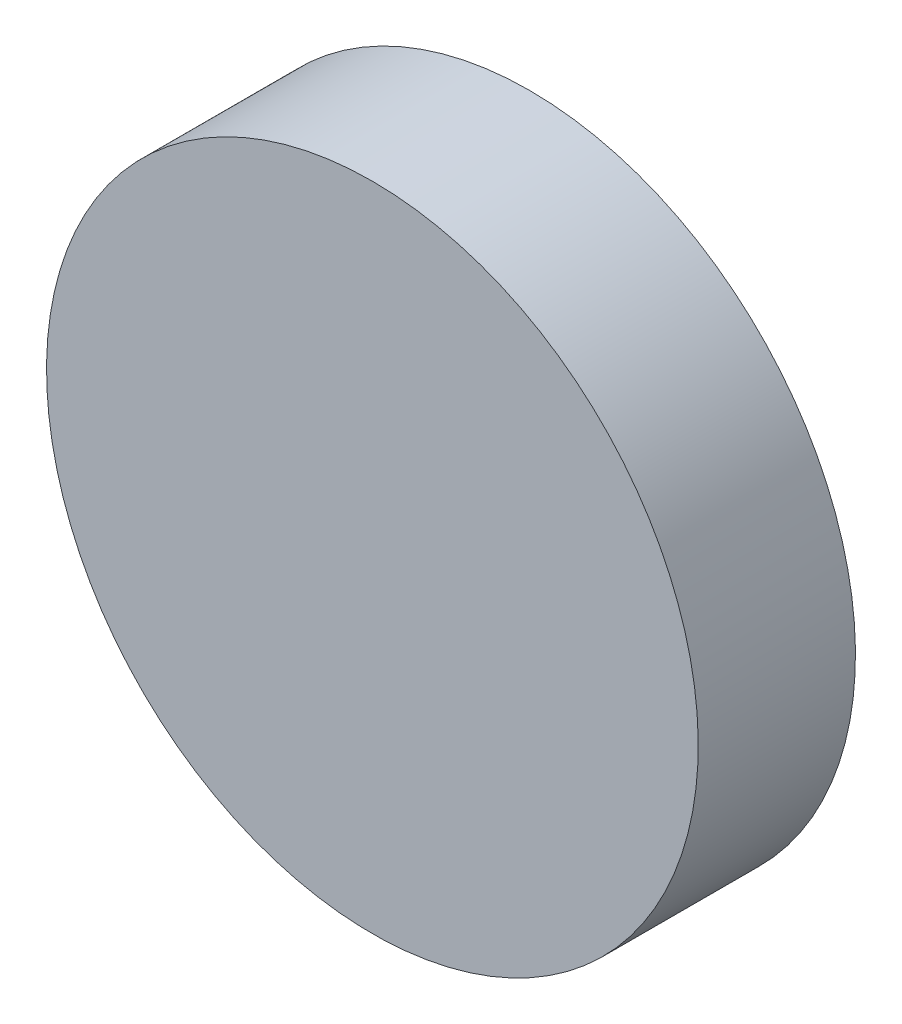
SolidWorks part; units mm, degrees
ref_plane "Front Plane" through (0, 0, 0) normal (0, 0, 1) x (1, 0, 0)
ref_plane "Top Plane" through (0, 0, 0) normal (0, 1, 0) x (1, 0, 0)
ref_plane "Right Plane" through (0, 0, 0) normal (1, 0, 0) x (0, 0, -1)
ref_plane "Plane1" through (0, 0, 0) normal (0, -1, 0) x (1, 0, 0)
sketch "Sketch1" plane through (0, 0, 0) normal (0, -1, 0) x (1, 0, 0)
  line L0 (40, -6.5) -> (0, -6.5)
  line L1 (0, -6.5) -> (0, -25.8)
  line L2 (0, -25.8) -> (40, -25.8)
  line L3 (40, -25.8) -> (40, -6.5)
  line L4 (0, -6.5) -> (0, -25.8) construction
revolve "Revolve1" add sketch "Sketch1" angle 360 about L4
sketch "Sketch2" plane through (0, 0, -6.5) normal (0, 0, 1) x (1, 0, 0)
  circle A0 centre (0, 0) radius 20
